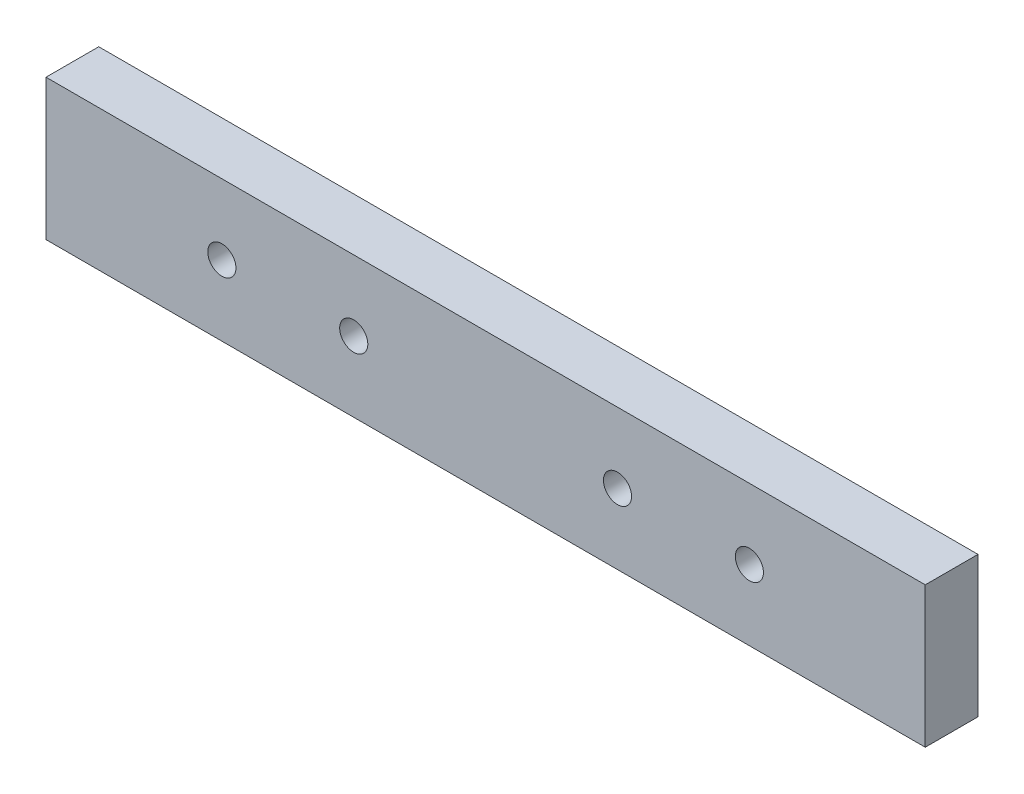
SolidWorks part; units mm, degrees
ref_plane "正面" through (0, 0, 0) normal (0, 0, 1) x (1, 0, 0)
ref_plane "平面" through (0, 0, 0) normal (0, 1, 0) x (1, 0, 0)
ref_plane "右側面" through (0, 0, 0) normal (1, 0, 0) x (0, 0, -1)
sketch "ｽｹｯﾁ1" plane through (0, 0, 0) normal (0, 0, 1) x (1, 0, 0)
  line L0 (35.4329, 0) -> (-35.4329, 0) construction
  line L1 (-50, 8) -> (50, 8)
  line L2 (-50, 8) -> (-50, -8)
  line L3 (-50, -8) -> (50, -8)
  line L4 (50, 8) -> (50, -8)
  line L5 (-50, 8) -> (50, -8) construction
  line L6 (-50, -8) -> (50, 8) construction
  line L7 (0, -13.093) -> (0, 13.093) construction
  circle A0 centre (30, 0) radius 1.6
  circle A1 centre (15, 0) radius 1.6
  circle A2 centre (-30, 0) radius 1.6
  circle A3 centre (-15, 0) radius 1.6
  point P0 (0, 0)
  dimension "D3" = 3.2
  dimension "D4" = 3.2
  dimension "D5" = 20
  dimension "D6" = 35
  dimension "D1" = 100
  dimension "D2" = 16
extrude "ﾎﾞｽ - 押し出し1" add sketch "ｽｹｯﾁ1" along normal blind 6
